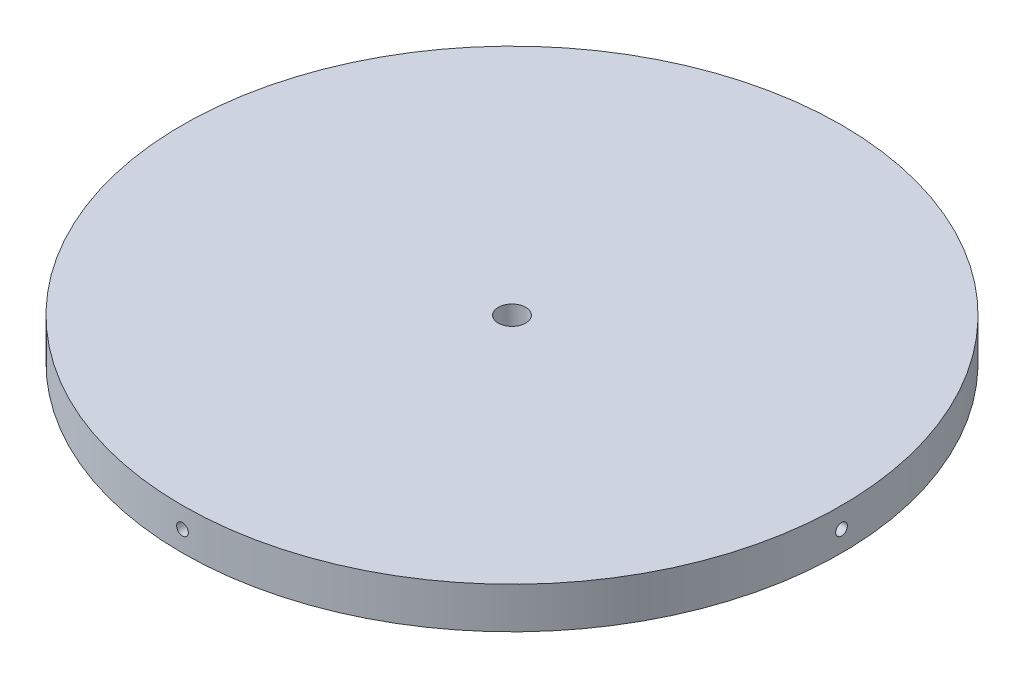
SolidWorks part; units mm, degrees
ref_plane "Front Plane" through (0, 0, 0) normal (0, 0, 1) x (1, 0, 0)
ref_plane "Top Plane" through (0, 0, 0) normal (0, 1, 0) x (1, 0, 0)
ref_plane "Right Plane" through (0, 0, 0) normal (1, 0, 0) x (0, 0, -1)
sketch "Sketch1" plane through (0, 0, 0) normal (0, 1, 0) x (1, 0, 0)
  circle A0 centre (0, 0) radius 76.1746
  circle A1 centre (0, 0) radius 3.175
  dimension "D1" = 152.3492
  dimension "D2" = 6.35
extrude "Boss-Extrude1" add sketch "Sketch1" along normal blind 9.525
ref_plane "Plane1" through (0, 0, -76.1746) normal (0, 0, -1) x (-1, 0, 0)
hole_wizard "Tap Drill for #6-32 Tap1" positions "Sketch2" profile "Sketch3" hole size "#6-32" standard "ANSI Inch"
sketch "Sketch2" plane through (0, 0, -76.1746) normal (0, 0, -1) x (-1, 0, 0)
  point P0 (0, 4.7625)
  dimension "D1" = 4.7625
sketch "Sketch3" plane through (0, 4.7625, -76.1746) normal (1, 0, 0) x (0, 1, 0)
  line L0 (0, 0) -> (0, 10.4647)
  line L1 (0, 10.4647) -> (1.3525, 9.652)
  line L2 (1.3525, 9.652) -> (1.3525, 0)
  line L5 (1.3525, 0) -> (0, 0)
  line L10 (0, 10.4647) -> (-1.3525, 9.652) construction
  line L11 (0, -6.35) -> (0, 107.95) construction
  dimension "Hole Dia." = 2.7051
  dimension "Hole Depth" = 9.652
  dimension "Drill Angle" = 118
pattern_circular "CirPattern1" count 4 over 360 about axis through (0, 9.525, 0) along (0, 1, 0) of "Tap Drill for #6-32 Tap1"
equation "\"AB_Coupler_OD_Length\"= 1in"
equation "\"AB_Coupling_Section_Length\"= 0.375in"
equation "\"AB_Coupler_Length\"= \"AB_Coupler_OD_Length\" + \"AB_Coupling_Section_Length\" * 2"
equation "\"Cutout_Angle\" = 60"
equation "\"AB_Coupler_Num_Screws\"= 6"
equation "\"Num_Cutouts\" = 4"
equation "\"AB_Coupler_OD\"= 6.17in"
equation "\"AB_Coupler_ID\"= 5.75in"
equation "\"AB_Coupler_Surface_Diameter\"= 5.998in"
equation "\"AB_Coupling_Screw_Diameter\"= 0.1065in"
equation "\"Aft_Section_Length\"= 40in"
equation "\"Aft_Lower_Length\"= 20in"
equation "\"Aft_Upper_Length\"= \"Aft_Section_Length\" - \"Aft_Lower_Length\" - \"AB_Coupler_OD_Length\""
equation "\"Mid_Coupler_Length\" = 10in"
equation "\"Lead_Screw_Dist\" = 2.25in"
equation "\"Lead_Screw_Diam\" = (27/64)*1in"
equation "\"Lead_Screw_Length\" = (\"Mid_Coupler_Length\" + 2*0.375in + 2*0.5in)"
equation "\"Bodytube_OD\" = 6.17in"
equation "\"Bodytube_ID\" = 5.998in"
equation "\"Paddle_Pin_Radius\" = 2.7in"
equation "\"D1@Sketch1\"=\"AB_Coupler_Surface_Diameter\""
equation "\"D2@Sketch1\"=1/4in"
equation "\"D1@Sketch2\"=.375/2"
